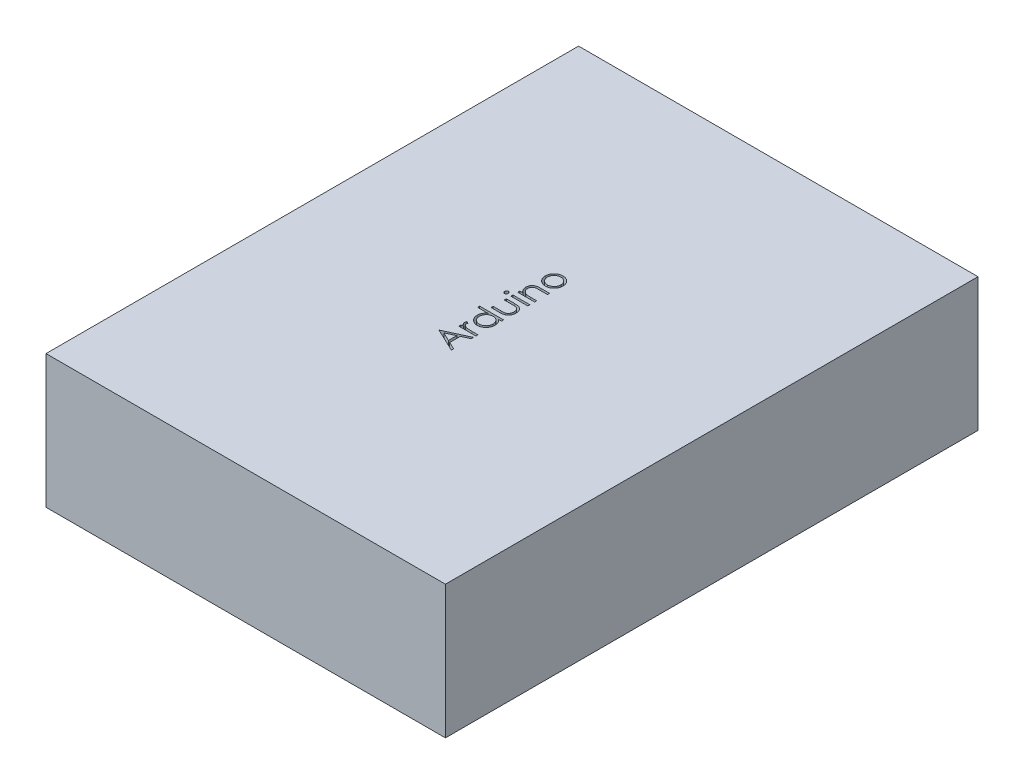
SolidWorks part; units mm, degrees
ref_plane "Front Plane" through (0, 0, 0) normal (0, 0, 1) x (1, 0, 0)
ref_plane "Top Plane" through (0, 0, 0) normal (0, 1, 0) x (1, 0, 0)
ref_plane "Right Plane" through (0, 0, 0) normal (1, 0, 0) x (0, 0, -1)
sketch "Sketch1" plane through (0, 0, 0) normal (0, 1, 0) x (1, 0, 0)
  line L1 (-30, 40) -> (30, 40)
  line L2 (-30, 40) -> (-30, -40)
  line L3 (-30, -40) -> (30, -40)
  line L4 (30, 40) -> (30, -40)
  line L5 (-30, 40) -> (30, -40) construction
  line L6 (-30, -40) -> (30, 40) construction
  point P0 (0, 0)
  dimension "D1" = 60
  dimension "D2" = 80
extrude "Boss-Extrude1" add sketch "Sketch1" along normal blind 20
sketch "Sketch2" plane through (0, 20, 0) normal (0, 1, 0) x (1, 0, 0)
  line L0 (0, -40) -> (0, 40) construction
  line L1 (-30, -40) -> (30, -40) construction
  line L2 (30, 40) -> (-30, 40) construction
  text T0 "Arduino"
extrude "Cut-Extrude1" cut sketch "Sketch2" against normal blind 2
